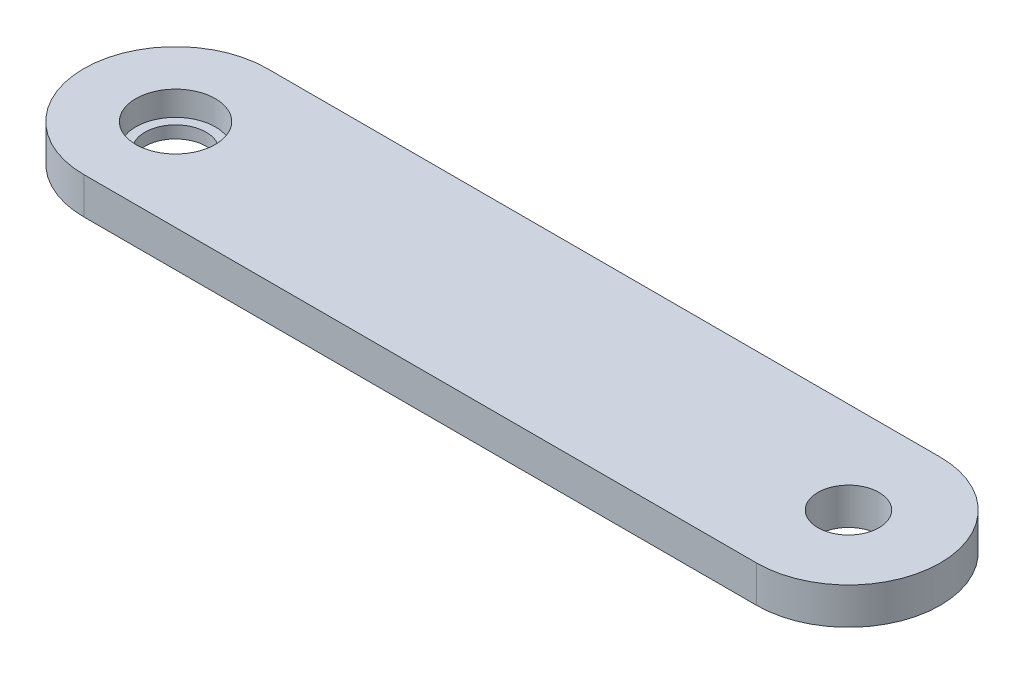
SolidWorks part; units mm, degrees
ref_plane "Front Plane" through (0, 0, 0) normal (0, 0, 1) x (1, 0, 0)
ref_plane "Top Plane" through (0, 0, 0) normal (0, 1, 0) x (1, 0, 0)
ref_plane "Right Plane" through (0, 0, 0) normal (1, 0, 0) x (0, 0, -1)
sketch "Sketch2" plane through (0, 0, 0) normal (0, 1, 0) x (1, 0, 0)
  line L1 (-45, 15) -> (65, 15)
  line L3 (-45, -15) -> (65, -15)
  arc A0 (-45, 15) -> (-45, -15) centre (-45, 0) ccw
  arc A1 (65, -15) -> (65, 15) centre (65, 0) ccw
  circle A2 centre (-45, 0) radius 5
  circle A3 centre (65, 0) radius 5
  point P0 (0, 0)
extrude "Boss-Extrude1" add sketch "Sketch2" along normal blind 6
sketch "Sketch3" plane through (0, 6, 0) normal (0, 1, 0) x (1, 0, 0)
  circle A0 centre (-45, 0) radius 6.5
extrude "Cut-Extrude1" cut sketch "Sketch3" against normal blind 4
